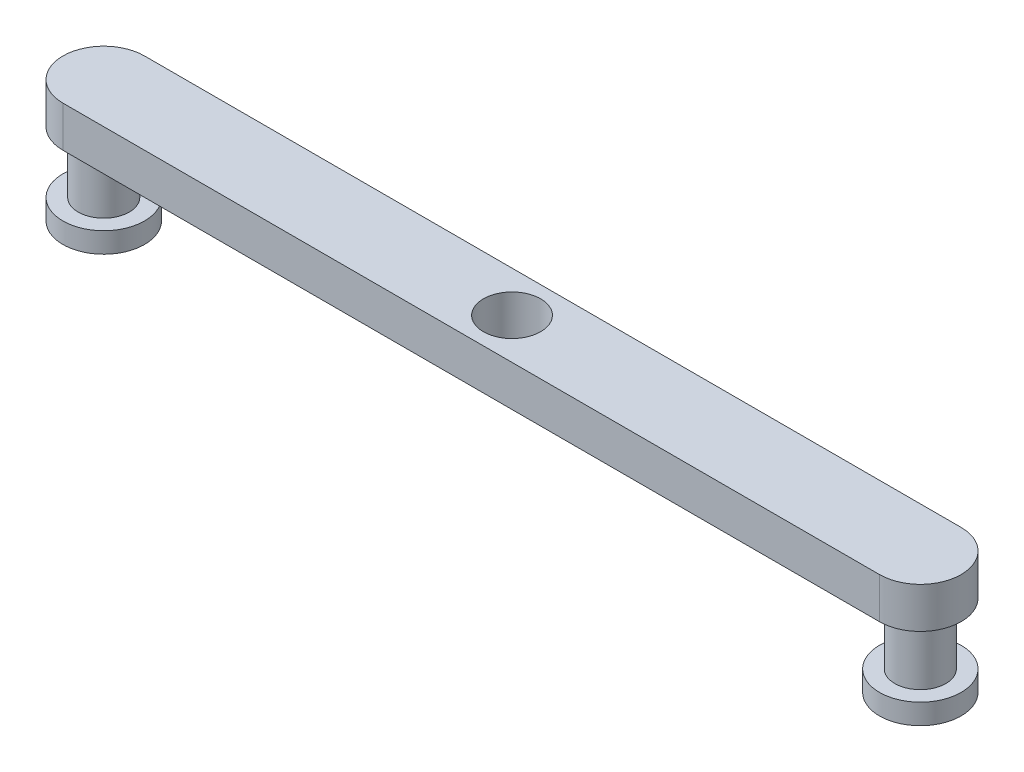
SolidWorks part; units mm, degrees
ref_plane "Front Plane" through (0, 0, 0) normal (0, 0, 1) x (1, 0, 0)
ref_plane "Top Plane" through (0, 0, 0) normal (0, 1, 0) x (1, 0, 0)
ref_plane "Right Plane" through (0, 0, 0) normal (1, 0, 0) x (0, 0, -1)
sketch "Sketch1" plane through (0, 0, 0) normal (0, 1, 0) x (1, 0, 0)
  line L0 (0, 0) -> (-50.8, 0)
  line L1 (0, 0) -> (50.8, 0)
  line L2 (-50.8, -5.08) -> (50.8, -5.08)
  line L3 (-50.8, 5.08) -> (50.8, 5.08)
  arc A0 (-50.8, 5.08) -> (-50.8, -5.08) centre (-50.8, 0) ccw
  arc A1 (50.8, -5.08) -> (50.8, 5.08) centre (50.8, 0) ccw
  dimension "D1" = 101.6
sketch "Sketch2" plane through (0, 0, 0) normal (0, 1, 0) x (1, 0, 0)
  line L0 (-50.8, -5.08) -> (50.8, -5.08)
  line L1 (-50.8, 5.08) -> (50.8, 5.08)
  arc A0 (-50.8, 5.08) -> (-50.8, -5.08) centre (-50.8, 0) ccw
  arc A1 (50.8, -5.08) -> (50.8, 5.08) centre (50.8, 0) ccw
extrude "Boss-Extrude1" add sketch "Sketch2" along normal blind 5.08
sketch "Sketch3" plane through (0, 0, 0) normal (0, -1, 0) x (1, 0, 0)
  circle A0 centre (-50.8, 0) radius 3.175
  circle A1 centre (50.8, 0) radius 3.175
extrude "Boss-Extrude2" add sketch "Sketch3" along normal blind 7.62
sketch "Sketch4" plane through (0, -7.62, 0) normal (0, -1, 0) x (1, 0, 0)
  circle A0 centre (-50.8, 0) radius 5.08
  circle A1 centre (50.8, 0) radius 5.08
extrude "Boss-Extrude3" add sketch "Sketch4" along normal blind 2.54
sketch "Sketch5" plane through (0, 0, 0) normal (0, 1, 0) x (1, 0, 0)
  circle A0 centre (0, 0) radius 3.302
sketch "Sketch7" plane through (0, 0, 0) normal (0, 1, 0) x (1, 0, 0)
  circle A0 centre (0, 0) radius 3.556
extrude "Cut-Extrude1" cut sketch "Sketch7" along normal up to vertex (5.08 mm away)
